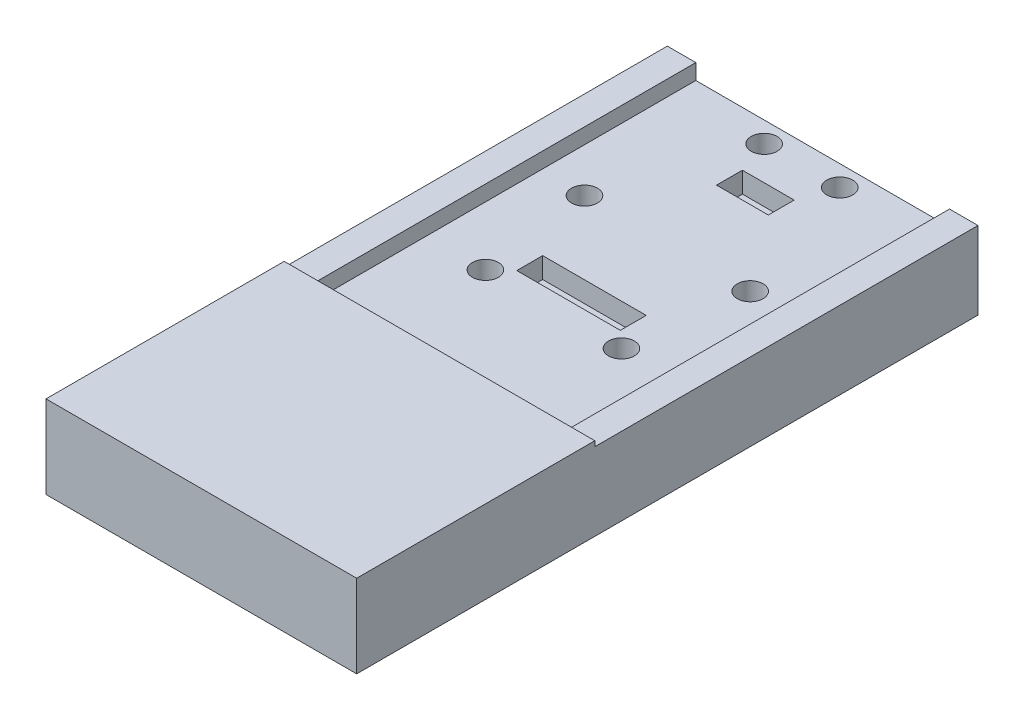
SolidWorks part; units mm, degrees
ref_plane "Front Plane" through (0, 0, 0) normal (0, 0, 1) x (1, 0, 0)
ref_plane "Top Plane" through (0, 0, 0) normal (0, 1, 0) x (1, 0, 0)
ref_plane "Right Plane" through (0, 0, 0) normal (1, 0, 0) x (0, 0, -1)
sketch "Sketch1" plane through (0, 0, 0) normal (0, 1, 0) x (1, 0, 0)
  line L0 (0, 30) -> (0, -30) construction
  line L1 (-15, 30) -> (15, 30)
  line L2 (-15, 30) -> (-15, -30)
  line L3 (-15, -30) -> (15, -30)
  line L4 (15, 30) -> (15, -30)
  circle A0 centre (-8, 15) radius 1.25
  circle A1 centre (8, 15) radius 1.25
  dimension "5" = 2.5
  dimension "D1" = 60
  dimension "D2" = 30
  dimension "D3" = 30
  dimension "D4" = 8
  dimension "D5" = 15
extrude "Boss-Extrude1" add sketch "Sketch1" against normal blind 6
ref_plane "Plane1" through (0, -6, 0) normal (0, -1, 0) x (-1, 0, 0)
sketch "Sketch2" plane through (0, -6, 0) normal (0, -1, 0) x (-1, 0, 0)
  circle A0 centre (-8, 15) radius 2.25
  circle A1 centre (8, 15) radius 2.25
  dimension "D1" = 4.5
extrude "Cut-Extrude1" cut sketch "Sketch2" against normal blind 2
sketch "Sketch3" plane through (0, 0, 0) normal (0, 1, 0) x (1, 0, 0)
  line L0 (0, 36.5143) -> (0, -37.671) construction
  line L1 (-15, -30) -> (15, -30) construction
  line L2 (-15, 30) -> (-12.25, 30)
  line L3 (-15, 30) -> (-15, -30)
  line L4 (-15, -30) -> (-12.25, -30)
  line L5 (-12.25, 30) -> (-12.25, -30)
  line L7 (15, 30) -> (12.25, 30)
  line L8 (15, 30) -> (15, -30)
  line L9 (15, -30) -> (12.25, -30)
  line L10 (12.25, 30) -> (12.25, -30)
  dimension "D1" = 12.25
extrude "Boss-Extrude2" add sketch "Sketch3" along normal blind 1.5
sketch "Sketch4" plane through (0, 0, 0) normal (0, 1, 0) x (1, 0, 0)
  line L0 (0, 37.8943) -> (0, -36.8227) construction
  line L2 (-2.5, 24.75) -> (2.5, 24.75)
  line L3 (-2.5, 24.75) -> (-2.5, 22.25)
  line L4 (-2.5, 22.25) -> (2.5, 22.25)
  line L5 (2.5, 24.75) -> (2.5, 22.25)
  line L6 (-5, 7.96) -> (5, 7.96)
  line L7 (-5, 7.96) -> (-5, 5.46)
  line L8 (-5, 5.46) -> (5, 5.46)
  line L9 (5, 7.96) -> (5, 5.46)
  circle A0 centre (-3.65, 28) radius 1.25
  circle A1 centre (3.65, 28) radius 1.25
  circle A2 centre (-6.57, 4) radius 1.25
  circle A3 centre (6.57, 4) radius 1.25
  point P11 (-2.5, 23.5)
  point P20 (-5, 6.71)
  dimension "D2" = 2.5
  dimension "D9" = 10
  dimension "D1" = 28
  dimension "D3" = 2.5
  dimension "D4" = 5
  dimension "D5" = 4.5
  dimension "D6" = 7.3
  dimension "D7" = 4
  dimension "D8" = 13.14
  dimension "D10" = 2.5
  dimension "D11" = 2.71
extrude "Cut-Extrude2" cut sketch "Sketch4" against normal blind 2
sketch "Sketch5" plane through (0, 0, 0) normal (0, 1, 0) x (1, 0, 0)
  line L0 (-15, 30) -> (-15, -30) construction
  line L1 (-15, -7) -> (15, -7)
  line L2 (-15, -7) -> (-15, -30)
  line L3 (-15, -30) -> (15, -30)
  line L4 (15, -7) -> (15, -30)
  dimension "D1" = 7
extrude "Boss-Extrude3" add sketch "Sketch5" along normal blind 2
